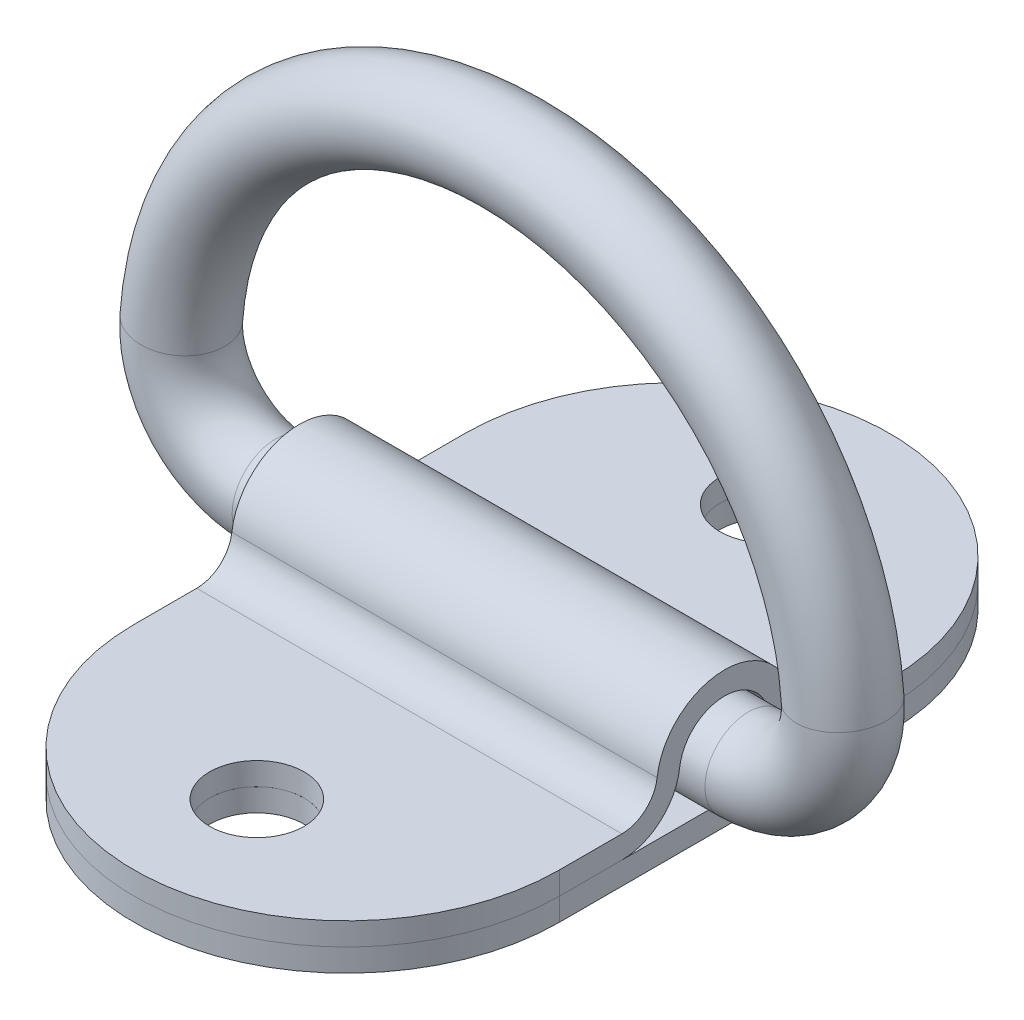
SolidWorks part; units mm, degrees
ref_plane "Front Plane" through (0, 0, 0) normal (0, 0, 1) x (1, 0, 0)
ref_plane "Top Plane" through (0, 0, 0) normal (0, 1, 0) x (1, 0, 0)
ref_plane "Right Plane" through (0, 0, 0) normal (1, 0, 0) x (0, 0, -1)
sketch "Sketch1" plane through (0, 0, 0) normal (0, 0, 1) x (1, 0, 0)
  line L0 (-15.8836, 0) -> (15.8836, 0) construction
  line L1 (-15.8836, 2.921) -> (15.8836, 2.921) construction
  circle A0 centre (0, 0) radius 2.921 construction
  circle A1 centre (0, 27.4955) radius 2.921 construction
  arc A2 (-15.8836, 0) -> (-22.2177, 6.7999) centre (-15.8836, 6.35) cw construction
  arc A3 (15.8836, 0) -> (22.2177, 6.7999) centre (15.8836, 6.35) ccw construction
  arc A4 (-22.2177, 6.7999) -> (22.2177, 6.7999) centre (0, 5.2219) cw construction
  arc A5 (15.8836, 2.921) -> (19.304, 6.5929) centre (15.8836, 6.35) ccw construction
  arc A6 (-15.8836, 2.921) -> (-19.304, 6.5929) centre (-15.8836, 6.35) cw construction
  arc A7 (-19.304, 6.5929) -> (19.304, 6.5929) centre (0, 5.2219) cw construction
  point P9 (0, 0)
  point P13 (0, 27.4955)
  point P14 (0, 2.921)
  point P15 (0, -2.921)
  point P16 (0, 24.5745)
  point P17 (0, 30.4165)
  point P21 (0, 2.921)
  point P27 (0, 24.5745)
  dimension "Ring Thickness" = 5.842
  dimension "Ring Corner Rad" = 6.35
  dimension "Ring Height" = 33.3375
  dimension "Inner Ring Width" = 38.608
sketch "Sketch2" plane through (0, 0, 0) normal (1, 0, 0) x (0, 0, -1)
  line L0 (-17.145, -3.048) -> (17.145, -3.048) construction
  line L1 (-25.4, -3.048) -> (-25.4, -4.572) construction
  line L2 (-25.4, -3.048) -> (25.4, -3.048) construction
  line L3 (25.4, -3.048) -> (25.4, -1.524) construction
  line L4 (25.4, -1.524) -> (6.9002, -1.524) construction
  line L5 (-25.4, -3.048) -> (-25.4, -1.524) construction
  line L6 (-25.4, -1.524) -> (-6.9002, -1.524) construction
  line L7 (-17.145, -1.524) -> (-17.145, -3.048) construction
  line L8 (17.145, -1.524) -> (17.145, -3.048) construction
  line L9 (-25.4, -4.572) -> (25.4, -4.572) construction
  line L10 (25.4, -4.572) -> (25.4, -3.048) construction
  circle A0 centre (0, 0) radius 2.921 construction
  circle A1 centre (0, 0) radius 3.048 construction
  arc A3 (3.0247, 0.3758) -> (6.9002, -3.048) centre (6.9002, 0.8572) ccw construction
  arc A4 (-3.0247, 0.3758) -> (-6.9002, -3.048) centre (-6.9002, 0.8572) cw construction
  arc A5 (6.9002, -1.524) -> (4.5371, 0.5637) centre (6.9002, 0.8572) cw construction
  arc A6 (-6.9002, -1.524) -> (-4.5371, 0.5637) centre (-6.9002, 0.8572) ccw construction
  arc A7 (-4.5371, 0.5637) -> (4.5371, 0.5637) centre (0, 0) cw construction
  point P8 (0, -3.048)
  point P13 (-25.4, -3.048)
  point P30 (0, -3.048)
  dimension "D1" = 6.096
  dimension "D4" = 2.3813
  dimension "Base Height" = 1.524
  dimension "Mounting Hole Center to Center Length" = 34.29
  dimension "Base Length" = 50.8
  dimension "D6" = 1.524
sketch "Sketch3" plane through (0, 0, 0) normal (0, 1, 0) x (1, 0, 0)
  line L0 (0, -25.4) -> (0, 25.4) construction
  line L1 (-14.2875, -11.1125) -> (-14.2875, 11.1125) construction
  line L3 (14.2875, 11.1125) -> (14.2875, -11.1125) construction
  circle A0 centre (0, 17.145) radius 3.175 construction
  circle A1 centre (0, -17.145) radius 3.175 construction
  arc A2 (-14.2875, 11.1125) -> (14.2875, 11.1125) centre (0, 11.1125) cw construction
  arc A3 (-14.2875, -11.1125) -> (14.2875, -11.1125) centre (0, -11.1125) ccw construction
  point P13 (-14.2875, 0)
  point P14 (14.2875, 0)
  point P16 (0, 25.4)
  dimension "Mounting Hole Diameter" = 6.35
  dimension "Base Width" = 28.575
sketch "Sketch4" plane through (0, 0, 0) normal (1, 0, 0) x (0, 0, -1)
  line L0 (-25.4, -3.048) -> (25.4, -3.048) construction
  line L1 (25.4, -3.048) -> (25.4, -1.524) construction
  line L2 (25.4, -1.524) -> (6.9002, -1.524) construction
  line L3 (-25.4, -3.048) -> (-25.4, -1.524) construction
  line L4 (-25.4, -1.524) -> (-6.9002, -1.524) construction
  line L5 (-25.4, -3.048) -> (-6.9002, -3.048)
  line L6 (25.4, -3.048) -> (25.4, -1.524)
  line L7 (25.4, -1.524) -> (6.9002, -1.524)
  line L8 (-25.4, -3.048) -> (-25.4, -1.524)
  line L9 (-25.4, -1.524) -> (-6.9002, -1.524)
  line L10 (6.9002, -3.048) -> (25.4, -3.048)
  circle A0 centre (0, 0) radius 3.048 construction
  arc A1 (-6.9002, -3.048) -> (-3.0247, 0.3758) centre (-6.9002, 0.8572) ccw construction
  arc A2 (3.0247, 0.3758) -> (6.9002, -3.048) centre (6.9002, 0.8572) ccw construction
  arc A3 (4.5371, 0.5637) -> (6.9002, -1.524) centre (6.9002, 0.8572) ccw construction
  arc A4 (4.5371, 0.5637) -> (-4.5371, 0.5637) centre (0, 0) ccw construction
  arc A5 (-6.9002, -1.524) -> (-4.5371, 0.5637) centre (-6.9002, 0.8572) ccw construction
  arc A6 (3.0247, 0.3758) -> (-3.0247, 0.3758) centre (0, 0) ccw
  arc A7 (-6.9002, -3.048) -> (-3.0247, 0.3758) centre (-6.9002, 0.8572) ccw
  arc A8 (3.0247, 0.3758) -> (6.9002, -3.048) centre (6.9002, 0.8572) ccw
  arc A9 (4.5371, 0.5637) -> (6.9002, -1.524) centre (6.9002, 0.8572) ccw
  arc A10 (4.5371, 0.5637) -> (-4.5371, 0.5637) centre (0, 0) ccw
  arc A11 (-6.9002, -1.524) -> (-4.5371, 0.5637) centre (-6.9002, 0.8572) ccw
extrude "Boss-Extrude1" add sketch "Sketch4" along normal up to vertex (14.2875 mm away) and the other way up to vertex (14.2875 mm away) up to point (14.2875, 0, 0) other way up to point (-14.2875, 0, 0)
sketch "Sketch5" plane through (0, 0, 0) normal (1, 0, 0) x (0, 0, -1)
  line L1 (-25.4, -4.572) -> (25.4, -4.572)
  line L2 (-25.4, -4.572) -> (-25.4, -3.048)
  line L3 (-25.4, -3.048) -> (25.4, -3.048)
  line L4 (25.4, -4.572) -> (25.4, -3.048)
extrude "Boss-Extrude2" add sketch "Sketch5" along normal up to vertex (14.2875 mm away) and the other way up to vertex (14.2875 mm away) separate body up to point (14.2875, 0, 0) other way up to point (-14.2875, 0, 0)
sketch "Sketch6" plane through (0, 0, 0) normal (0, 1, 0) x (1, 0, 0)
  line L0 (-14.2875, -11.1125) -> (-14.2875, 11.1125) construction
  line L1 (14.2875, 11.1125) -> (14.2875, -11.1125) construction
  line L2 (-14.2875, -11.1125) -> (-14.2875, 11.1125)
  line L3 (14.2875, 11.1125) -> (14.2875, -11.1125)
  arc A0 (-14.2875, -11.1125) -> (14.2875, -11.1125) centre (0, -11.1125) ccw construction
  arc A1 (14.2875, 11.1125) -> (-14.2875, 11.1125) centre (0, 11.1125) ccw construction
  arc A2 (-14.2875, -11.1125) -> (14.2875, -11.1125) centre (0, -11.1125) ccw
  arc A3 (14.2875, 11.1125) -> (-14.2875, 11.1125) centre (0, 11.1125) ccw
extrude "Cut-Extrude1" cut sketch "Sketch6" against normal through all flip side to cut
sketch "Sketch7" plane through (0, 0, 0) normal (0, 1, 0) x (1, 0, 0)
  circle A0 centre (0, -17.145) radius 3.175 construction
  circle A1 centre (0, 17.145) radius 3.175 construction
  circle A2 centre (0, -17.145) radius 3.175
  circle A3 centre (0, 17.145) radius 3.175
extrude "Cut-Extrude2" cut sketch "Sketch7" against normal through all
sketch "Sketch8" plane through (0, 0, 0) normal (1, 0, 0) x (0, 0, -1)
  circle A0 centre (0, 0) radius 2.921 construction
  circle A1 centre (0, 0) radius 2.921
sketch "Sketch9" plane through (0, 0, 0) normal (0, 0, 1) x (1, 0, 0)
  line L0 (-15.8836, 0) -> (15.8836, 0) construction
  line L1 (-15.8836, 0) -> (15.8836, 0)
  arc A0 (15.8836, 0) -> (22.2177, 6.7999) centre (15.8836, 6.35) ccw construction
  arc A1 (-22.2177, 6.7999) -> (-15.8836, 0) centre (-15.8836, 6.35) ccw construction
  arc A2 (22.2177, 6.7999) -> (-22.2177, 6.7999) centre (0, 5.2219) ccw construction
  arc A3 (15.8836, 0) -> (22.2177, 6.7999) centre (15.8836, 6.35) ccw
  arc A4 (-22.2177, 6.7999) -> (-15.8836, 0) centre (-15.8836, 6.35) ccw
  arc A5 (22.2177, 6.7999) -> (-22.2177, 6.7999) centre (0, 5.2219) ccw
sweep "Sweep1" add profiles "Sketch8" path "Sketch9"
ref_plane "Contact Plane 1" through (0, 30.4165, 0) normal (0, 1, 0) x (1, 0, 0)
equation "\"D6@Sketch2\" = \"Base Height@Sketch2\""
